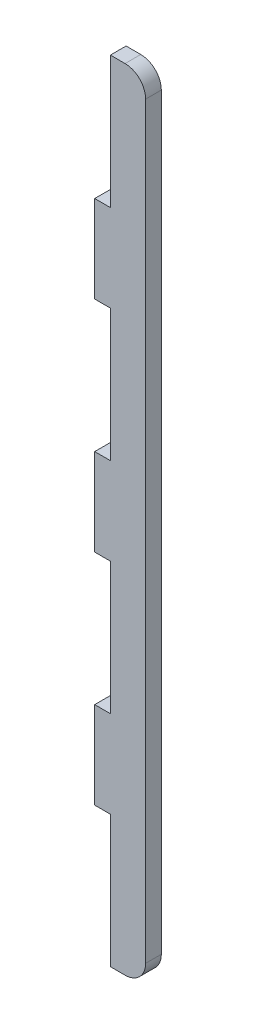
SolidWorks part; units mm, degrees
ref_plane "Front Plane" through (0, 0, 0) normal (0, 0, 1) x (1, 0, 0)
ref_plane "Top Plane" through (0, 0, 0) normal (0, 1, 0) x (1, 0, 0)
ref_plane "Right Plane" through (0, 0, 0) normal (1, 0, 0) x (0, 0, -1)
sketch "Model" plane through (0, 0, 0) normal (0, 0, 1) x (1, 0, 0)
  line L0 (0, 149.333) -> (0, 194.3335)
  line L1 (0, 0) -> (5, 0)
  line L2 (0, 0) -> (0, 45.0005)
  line L3 (0, 269) -> (5, 269)
  line L20 (12, 7) -> (12, 262)
  line L21 (0, 149.333) -> (-5.35, 149.333)
  line L22 (12, 134.5) -> (-89.6321, 134.5) construction
  line L23 (0, 119.667) -> (-5.35, 119.667)
  line L24 (-5.35, 149.333) -> (-5.35, 119.667)
  line L25 (-5.35, 223.9995) -> (-5.35, 194.3335)
  line L26 (0, 194.3335) -> (-5.35, 194.3335)
  line L27 (0, 223.9995) -> (-5.35, 223.9995)
  line L28 (0, 45.0005) -> (-5.35, 45.0005)
  line L29 (-5.35, 74.6665) -> (-5.35, 45.0005)
  line L30 (0, 74.6665) -> (-5.35, 74.6665)
  line L31 (0, 223.9995) -> (0, 269)
  line L32 (0, 74.6665) -> (0, 119.667)
  arc A2 (12, 262) -> (5, 269) centre (5, 262) ccw
  arc A3 (5, 0) -> (12, 7) centre (5, 7) ccw
  point P20 (-5.35, 134.5)
  dimension "D3" = 7
  dimension "D5" = 29.666
  dimension "D9" = 5.35
  dimension "D12" = 12
  dimension "D11" = 269
  dimension "D6" = 2
  dimension "D7" = 2
extrude "Boss-Extrude1" add sketch "Model" along normal blind 5.35
equation "\"mdfthick\"=5.35"
equation "\"D9@Model\"=\"mdfthick\""
equation "\"D1@Boss-Extrude1\"=\"mdfthick\""
